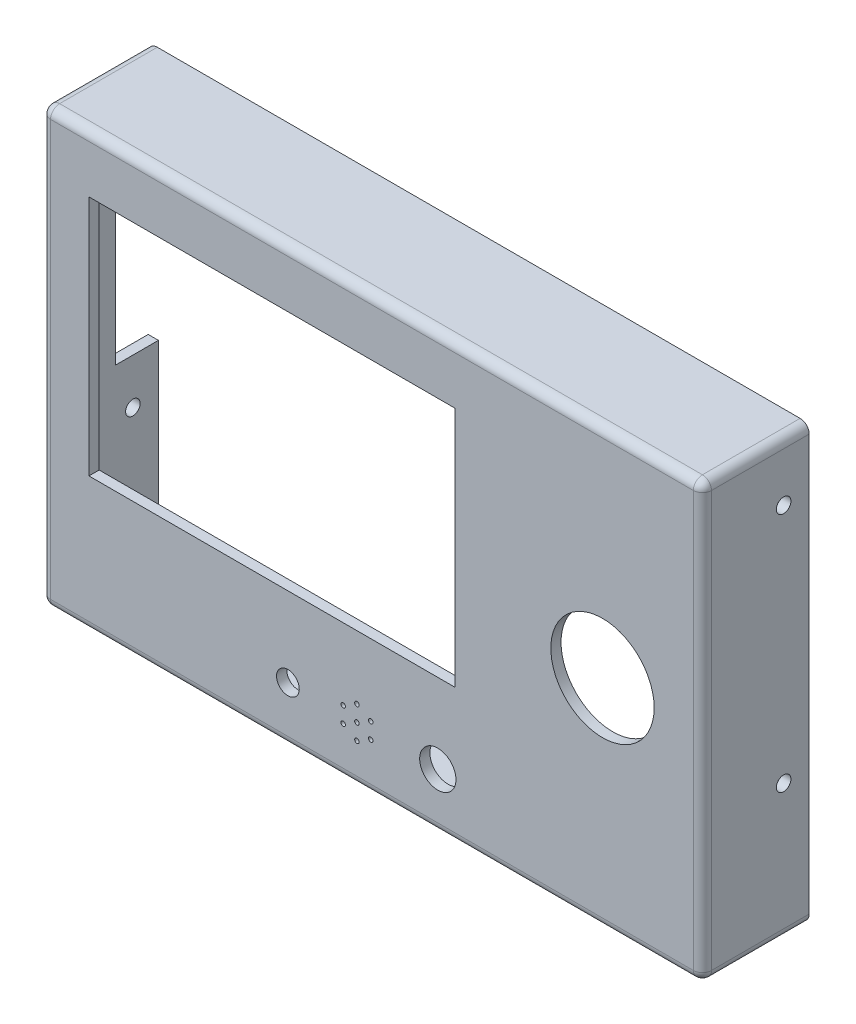
SolidWorks part; units mm, degrees
ref_plane "Top Plane" through (0, 0, 0) normal (0, 0, 1) x (1, 0, 0)
ref_plane "Front Plane" through (0, 0, 0) normal (0, 1, 0) x (1, 0, 0)
ref_plane "Right Plane" through (0, 0, 0) normal (1, 0, 0) x (0, 0, -1)
sketch "Face Sketch" plane through (0, 0, 0) normal (0, 0, 1) x (1, 0, 0)
  line L6 (-40.3, 35.2) -> (40.3, 35.2)
  line L7 (-40.3, 35.2) -> (-40.3, -18)
  line L8 (-40.3, -18) -> (40.3, -18)
  line L9 (40.3, 35.2) -> (40.3, -18)
  line L28 (-50.75, 47.75) -> (94.75, 47.75)
  line L29 (94.75, 47.75) -> (94.75, -47.75)
  line L30 (-50.75, -47.75) -> (94.75, -47.75)
  line L31 (-50.75, 47.75) -> (-50.75, -47.75)
  line L44 (-46.5, 43.5) -> (46.5, 43.5) construction
  line L45 (-46.5, 43.5) -> (-46.5, -43.5) construction
  line L46 (-46.5, -43.5) -> (46.5, -43.5) construction
  line L47 (46.5, 43.5) -> (46.5, -43.5) construction
  line L48 (0, -43.5) -> (0, 43.5) construction
  line L49 (-46.5, 0) -> (46.5, 0) construction
  circle A6 centre (-44, 41) radius 1.6 construction
  circle A7 centre (44, 41) radius 1.6 construction
  circle A8 centre (44, -24) radius 1.6 construction
  circle A9 centre (-44, -24) radius 1.6 construction
  circle A10 centre (18.7, -35.5) radius 0.5
  circle A19 centre (-38.35, -33.8096) radius 2.5 construction
  circle A20 centre (3.5, -35.5) radius 2.5
  circle A21 centre (36.5, -35.5) radius 4
  circle A22 centre (18.7, -32) radius 0.5
  circle A23 centre (21.7311, -33.75) radius 0.5
  circle A24 centre (21.7311, -37.25) radius 0.5
  circle A25 centre (18.7, -39) radius 0.5
  circle A26 centre (15.6689, -37.25) radius 0.5
  circle A27 centre (15.6689, -33.75) radius 0.5
  point P14 (0, 35.2)
  point P43 (18.7, -35.5)
  point P121 (0, 0)
  dimension "D12" = 3.2
  dimension "D17" = 1
  dimension "D24" = 5
  dimension "D28" = 5
  dimension "D20" = 8
  dimension "D4" = 65
  dimension "D5" = 88
  dimension "D9" = 53.2
  dimension "D10" = 93
  dimension "D11" = 87
  dimension "D18" = 10
  dimension "D19" = 8
  dimension "D29" = 3.5
  dimension "D15" = 8.3
  dimension "D16" = 9.6904
  dimension "D22" = 8.15
  dimension "D23" = 8
  dimension "D25" = 8
  dimension "D27" = 43
  dimension "D26" = 27.8
  dimension "D13" = 2.5
  dimension "D14" = 2.5
  dimension "D7" = 80.6
  dimension "D8" = 4.25
  dimension "D21" = 4.25
  dimension "Right Side Size" = 48.25
  dimension "D6" = 4.25
  dimension "D30" = 6
extrude "Face Extrude" add sketch "Face Sketch" along normal blind 2.25
sketch "Sketch1" plane through (0, 0, 0) normal (0, 0, 1) x (1, 0, 0)
  line L0 (94.75, 0) -> (72.75, 0) construction
  line L1 (94.75, -47.75) -> (94.75, 47.75) construction
  circle A0 centre (72.75, 0) radius 11.375
  dimension "D1" = 22.75
  dimension "D2" = 22
extrude "Stop Button Mounting Hole Cut" cut sketch "Sketch1" along normal through all
sketch "Walls Sketch" plane through (0, 0, 0) normal (0, 0, -1) x (-1, 0, 0)
  line L10 (-92.5, 45.5) -> (48.5, 45.5)
  line L15 (-94.75, 47.75) -> (50.75, 47.75)
  line L16 (-94.75, 47.75) -> (-94.75, -47.75)
  line L17 (-94.75, -47.75) -> (50.75, -47.75)
  line L18 (50.75, 47.75) -> (50.75, -47.75)
  line L19 (48.5, 45.5) -> (48.5, -45.5)
  line L20 (-92.5, -45.5) -> (48.5, -45.5)
  line L21 (-92.5, 45.5) -> (-92.5, -45.5)
  dimension "D1" = 2.25
extrude "Walls Extrude" add sketch "Walls Sketch" along normal blind 21.25
sketch "SD Card Access Sketch" plane through (-50.75, 0, 0) normal (-1, 0, 0) x (0, 0, 1)
  line L0 (-9.5, 47.75) -> (-9.5, 7.5) construction
  line L1 (2.25, 47.75) -> (-21.25, 47.75) construction
  line L3 (-21.25, 23) -> (-11.75, 23)
  line L4 (-21.25, 23) -> (-21.25, -8)
  line L5 (-21.25, -8) -> (-11.75, -8)
  line L6 (-11.75, 23) -> (-11.75, -8)
  line L7 (-21.25, -47.75) -> (-21.25, 47.75) construction
  line L8 (2.25, 47.75) -> (2.25, -47.75) construction
  line L10 (-9.5, 7.5) -> (-11.75, 7.5) construction
  dimension "D1" = 31
  dimension "D3" = 40.25
  dimension "D4" = 14
extrude "SD Card Cut" cut sketch "SD Card Access Sketch" against normal blind 2.5
fillet "Edge Radius" radius 2 8 edges at (-50.75, 0, 2.25) (94.75, 0, 2.25) (22, -47.75, 2.25) (22, 47.75, 2.25) (-50.75, 47.75, -9.5) (94.75, 47.75, -9.5) (94.75, -47.75, -9.5) (-50.75, -47.75, -9.5)
sketch "Top Connectors Sketch" plane through (0, 0, 0) normal (1, 0, 0) x (0, 0, -1)
  line L0 (15.625, 43.5) -> (21.25, 43.5) construction
  line L1 (21.25, 23) -> (21.25, 45.75) construction
  line L2 (15.625, 41) -> (21.25, 41) construction
  line L3 (15.625, 8.5) -> (21.25, 8.5) construction
  circle A0 centre (15.625, 35) radius 1.6
  circle A1 centre (15.625, -18) radius 1.6
  dimension "D6" = 3.2
  dimension "D1" = 5.625
  dimension "D2" = 35
  dimension "D3" = 43.5
  dimension "D4" = 2.5
  dimension "D5" = 32.5
extrude "Top Connectors Cut" cut sketch "Top Connectors Sketch" against normal through all and the other way through all
equation "\"Controller Clearance\"= 2mm"
equation "\"Shell Thickness\"= 2.25mm"
equation "\"Screen Clearance\"= 1mm"
equation "\"D15@Face Sketch\"=9.3-\"Screen Clearance\""
equation "\"PCB Hole Spacing X\"= 88mm"
equation "\"PCB Hole Spacing Y\"= 65mm"
equation "\"D5@Face Sketch\"=\"PCB Hole Spacing X\""
equation "\"D4@Face Sketch\"=\"PCB Hole Spacing Y\""
equation "\"Controller Size X\"= 93mm"
equation "\"Controller Size Y\"= 87mm"
equation "\"D11@Face Sketch\"=\"Controller Size Y\""
equation "\"D10@Face Sketch\"=\"Controller Size X\""
equation "\"Outside Fillet Radius\"= 2mm"
equation "\"D1@Edge Radius\"=\"Outside Fillet Radius\""
equation "\"Screen Height\"= 51.2mm"
equation "\"Screen Width\"= 78.6mm"
equation "\"D9@Face Sketch\"=\"Screen Height\"+2*\"Screen Clearance\""
equation "\"D7@Face Sketch\"=\"Screen Width\"+2*\"Screen Clearance\""
equation "\"SD Card Position\"= 22.5mm + 27/2.0mm + \"Shell Thickness\" + \"Controller Clearance\""
equation "\"SD Card Width\"= 31mm"
equation "\"D3@SD Card Access Sketch\"=\"SD Card Position\""
equation "\"D1@SD Card Access Sketch\"=\"SD Card Width\""
equation "\"D1@Walls Extrude\"=23.5-\"Shell Thickness\""
equation "\"D1@Face Extrude\"=\"Shell Thickness\""
equation "\"Top Mounting Hole Position\"= 2.5mm"
equation "\"Top Connector Y Position\"= 0.5 * \"Controller Size Y\" - \"Top Mounting Hole Position\" - 6"
equation "\"Standoff Height\"= 9 - \"Shell Thickness\""
equation "\"D1@Top Connectors Sketch\"=\"Standoff Height\" / 2 + \"Shell Thickness\""
equation "\"D2@Top Connectors Sketch\" = \"Top Connector Y Position\""
equation "\"D3@Top Connectors Sketch\" = \"Controller Size Y\" / 2"
equation "\"D4@Top Connectors Sketch\" = \"Top Mounting Hole Position\""
equation "\"D5@Top Connectors Sketch\" = \"PCB Hole Spacing Y\" / 2"
equation "\"Slip Fit Clearance\"= 0.2mm"
equation "\"D8@Face Sketch\"=\"Controller Clearance\"+\"Shell Thickness\""
equation "\"D21@Face Sketch\"=\"Controller Clearance\"+\"Shell Thickness\""
equation "\"Right Side Size@Face Sketch\"  = \"Controller Clearance\" + \"Shell Thickness\"+\"Stop Button Entension Size\""
equation "\"Stop Button Entension Size\"= 44mm"
equation "\"D2@Sketch1\"=\"Stop Button Entension Size\"/2"
equation "\"D1@Walls Sketch\"=\"Shell Thickness\""
equation "\"D6@Face Sketch\"=\"Controller Clearance\"+\"Shell Thickness\""
